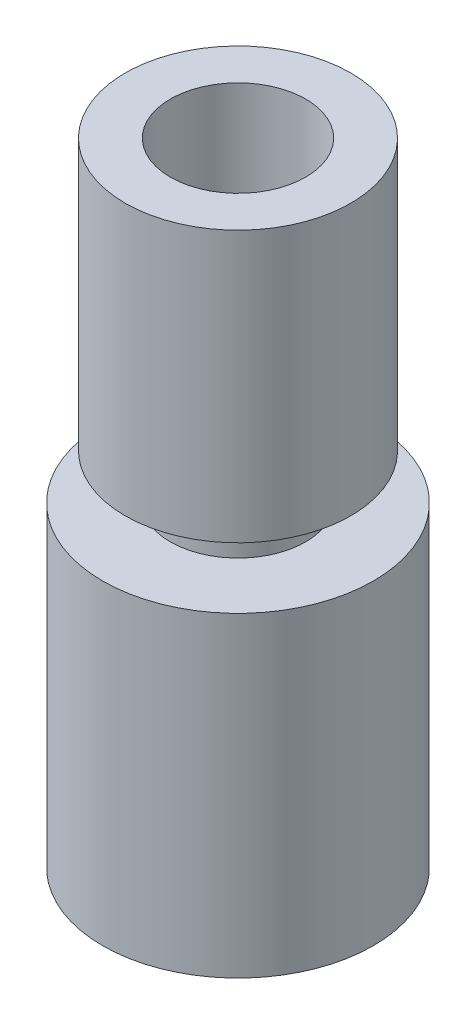
SolidWorks part; units mm, degrees
ref_plane "Alzado" through (0, 0, 0) normal (0, 0, 1) x (1, 0, 0)
ref_plane "Planta" through (0, 0, 0) normal (0, 1, 0) x (1, 0, 0)
ref_plane "Vista lateral" through (0, 0, 0) normal (1, 0, 0) x (0, 0, -1)
sketch "Croquis1" plane through (0, 0, 0) normal (0, 0, 1) x (1, 0, 0)
  line L0 (-3, 0) -> (-1.5, 0)
  line L1 (-3, 0) -> (-3, 7)
  line L2 (-1.5, 0) -> (-1.5, 3)
  line L3 (-1.5, 3) -> (0, 3)
  line L4 (-3, 7) -> (-1.5, 7)
  line L5 (-1.5, 7) -> (-1.5, 8)
  line L6 (-1.5, 8) -> (-2.5, 8)
  line L7 (-2.5, 8) -> (-2.5, 14)
  line L8 (-2.5, 14) -> (-1.5, 14)
  line L9 (-1.5, 14) -> (-1.5, 11)
  line L10 (-1.5, 11) -> (0, 11)
  line L11 (0, 11) -> (0, 3)
  dimension "D1" = 1.5
  dimension "D2" = 7
  dimension "D3" = 3
  dimension "D4" = 1.5
  dimension "D5" = 1.5
  dimension "D6" = 1
  dimension "D7" = 1
  dimension "D8" = 6
  dimension "D9" = 1
  dimension "D10" = 1.5
revolve "Revolución1" add sketch "Croquis1" angle 360 about L11
